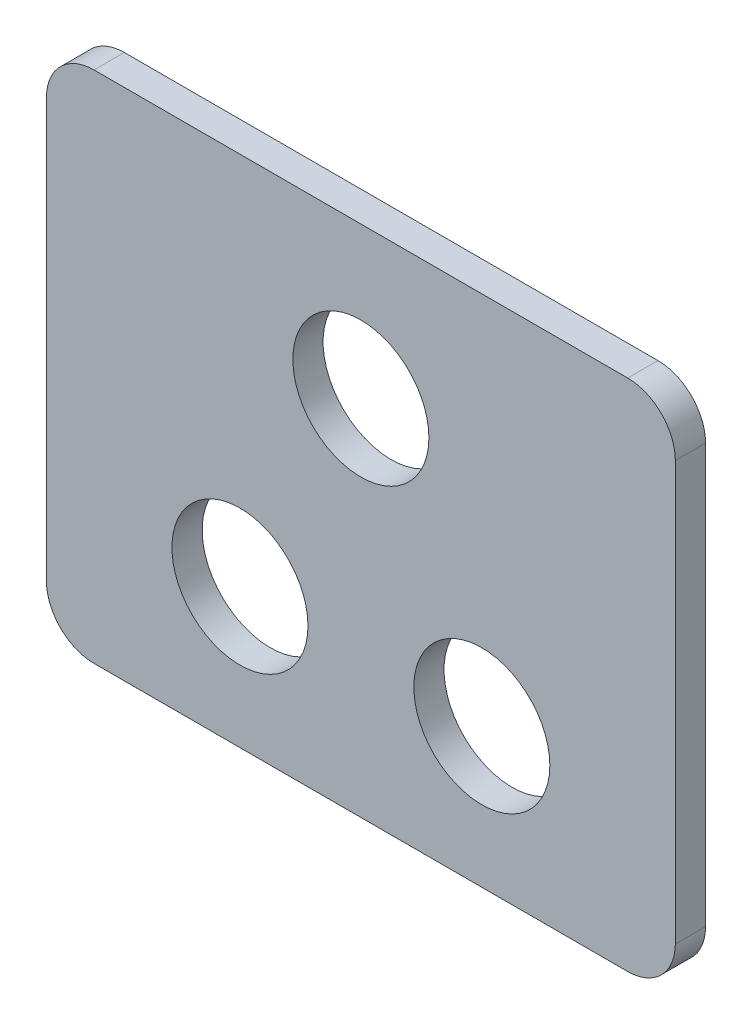
SolidWorks part; units mm, degrees
ref_plane "Front Plane" through (0, 0, 0) normal (0, 0, 1) x (1, 0, 0)
ref_plane "Top Plane" through (0, 0, 0) normal (0, 1, 0) x (1, 0, 0)
ref_plane "Right Plane" through (0, 0, 0) normal (1, 0, 0) x (0, 0, -1)
sketch "Sketch1" plane through (0, 0, 0) normal (0, 0, 1) x (1, 0, 0)
  line L1 (-80.0173, -25.3645) -> (32.0627, -25.3645)
  line L2 (-90.0173, -35.3645) -> (-90.0173, -123.3145)
  line L3 (-80.0173, -133.3145) -> (32.0627, -133.3145)
  line L4 (42.0627, -35.3645) -> (42.0627, -123.3145)
  arc A2 (-90.0173, -123.3145) -> (-80.0173, -133.3145) centre (-80.0173, -123.3145) ccw
  arc A3 (32.0627, -133.3145) -> (42.0627, -123.3145) centre (32.0627, -123.3145) ccw
  arc A4 (32.0627, -25.3645) -> (42.0627, -35.3645) centre (32.0627, -35.3645) cw
  arc A5 (-80.0173, -25.3645) -> (-90.0173, -35.3645) centre (-80.0173, -35.3645) ccw
  circle A6 centre (-23.9773, -57.1145) radius 14.2875
  circle A11 centre (1.4227, -104.0186) radius 14.2875
  circle A12 centre (-23.9773, -57.1145) radius 53.34
  circle A13 centre (-49.3773, -104.0186) radius 14.2875
  point P25 (-60.2337, -7.4362)
  dimension "D1" = 10
  dimension "D8" = 76.2
  dimension "D13" = 28.575
  dimension "D14" = 28.575
  dimension "D15" = 106.68
  dimension "D17" = 50.8
  dimension "D18" = 28.575
  dimension "D5" = 66.04
  dimension "D6" = 66.04
  dimension "D7" = 31.75
  dimension "D16" = 25.4
extrude "Boss-Extrude1" add sketch "Sketch1" along normal blind 6.35 contours A13 A12 A11 L1 A6 | A13 A12 L1 A5 L2 A2 L3 A3 L4 A4 A11
